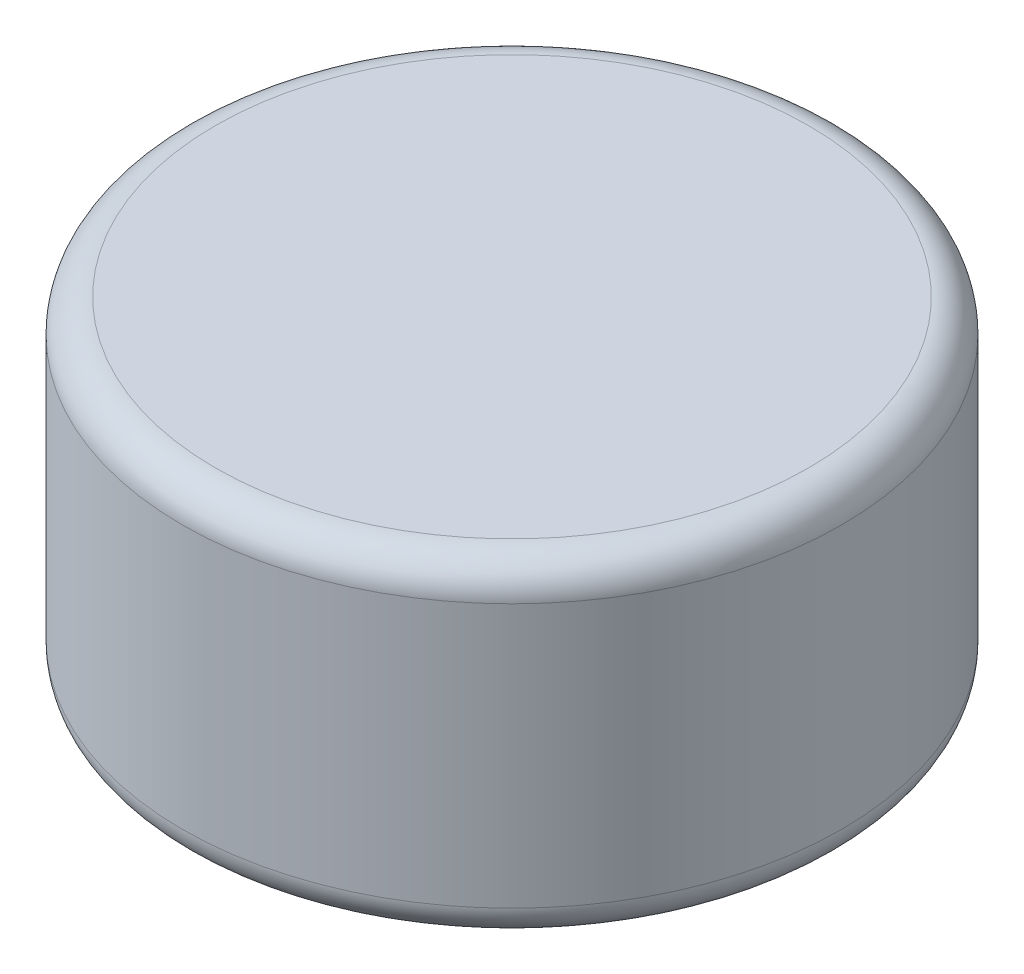
SolidWorks part; units mm, degrees
ref_plane "Front Plane" through (0, 0, 0) normal (0, 0, 1) x (1, 0, 0)
ref_plane "Top Plane" through (0, 0, 0) normal (0, 1, 0) x (1, 0, 0)
ref_plane "Right Plane" through (0, 0, 0) normal (1, 0, 0) x (0, 0, -1)
sketch "Sketch1" plane through (0, 0, 0) normal (0, 1, 0) x (1, 0, 0)
  circle A0 centre (0, 0) radius 5
  dimension "D1" = 10
extrude "Boss-Extrude1" add sketch "Sketch1" along normal blind 5
fillet "Fillet1" radius 0.5 2 edges at (0, 0, 5) (0, 5, 5)
